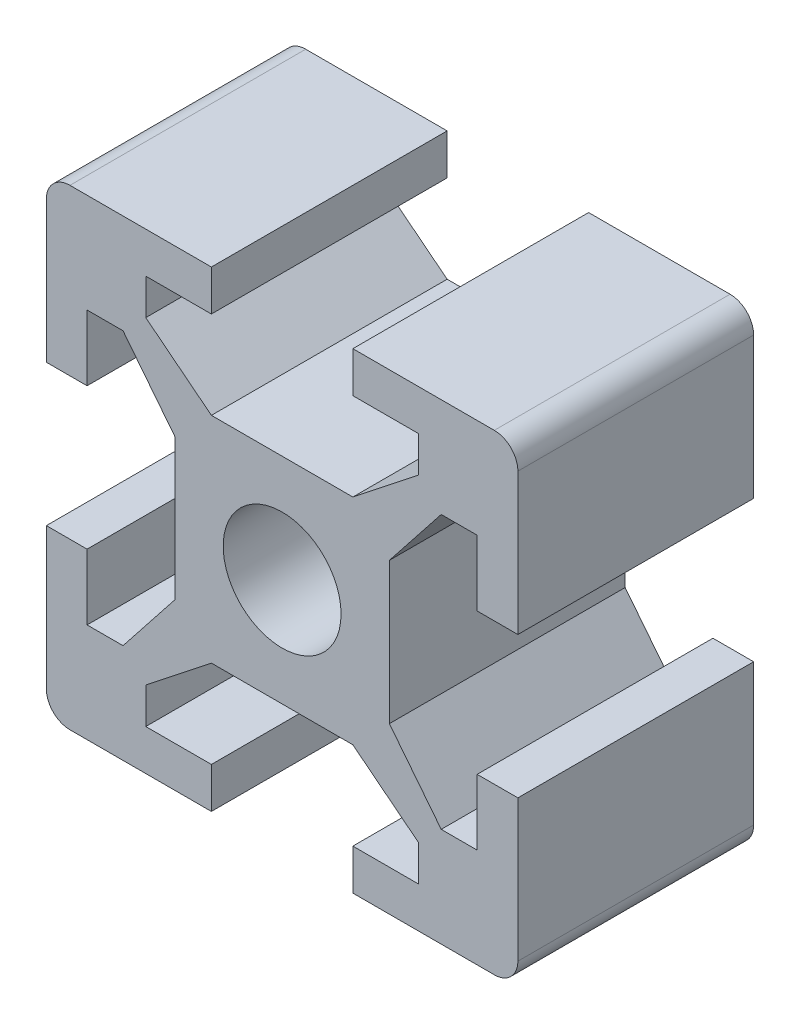
SolidWorks part; units mm, degrees
material "6063-T5"
ref_plane "Front Plane" through (0, 0, 0) normal (0, 0, 1) x (1, 0, 0)
ref_plane "Top Plane" through (0, 0, 0) normal (0, 1, 0) x (1, 0, 0)
ref_plane "Right Plane" through (0, 0, 0) normal (1, 0, 0) x (0, 0, -1)
sketch "Sketch1" plane through (0, 0, 0) normal (0, 0, 1) x (1, 0, 0)
  line L18 (0, 0) -> (0, 20.5117) construction
  line L39 (-10, 10) -> (-3, 10)
  line L41 (10, 10) -> (3, 10)
  line L43 (-10, 10) -> (-10, 3)
  line L45 (-10, -10) -> (-10, -3)
  line L47 (-10, -10) -> (-3, -10)
  line L49 (3, -10) -> (10, -10)
  line L51 (10, -10) -> (10, -3)
  line L53 (10, 3) -> (10, 10)
  line L55 (-3, 10) -> (-3, 8.2726)
  line L56 (-3, 8.2726) -> (-5.7838, 8.2726)
  line L57 (-5.7838, 8.2726) -> (-5.7838, 6.748)
  line L58 (-5.7838, 6.748) -> (-3, 4.5508)
  line L59 (-3, 4.5508) -> (3, 4.5508)
  line L60 (3, 10) -> (3, 8.2726)
  line L61 (3, 8.2726) -> (5.7838, 8.2726)
  line L62 (5.7838, 8.2726) -> (5.7838, 6.748)
  line L63 (5.7838, 6.748) -> (3, 4.5508)
  line L64 (10, 3) -> (8.2726, 3)
  line L65 (8.2726, 3) -> (8.2726, 5.7838)
  line L66 (8.2726, 5.7838) -> (6.748, 5.7838)
  line L67 (10, -3) -> (8.2726, -3)
  line L68 (8.2726, -3) -> (8.2726, -5.7838)
  line L69 (8.2726, -5.7838) -> (6.748, -5.7838)
  line L70 (4.55, -2.9994) -> (4.55, 3.0006)
  line L71 (4.55, -2.9994) -> (6.748, -5.7838)
  line L72 (4.55, 3.0006) -> (6.748, 5.7838)
  line L73 (3, -10) -> (3, -8.2726)
  line L74 (3, -8.2726) -> (5.7838, -8.2726)
  line L75 (5.7838, -8.2726) -> (5.7838, -6.748)
  line L76 (-3, -10) -> (-3, -8.2726)
  line L77 (-3, -8.2726) -> (-5.7838, -8.2726)
  line L78 (-5.7838, -8.2726) -> (-5.7838, -6.748)
  line L79 (2.9994, -4.55) -> (-3.0006, -4.55)
  line L80 (5.7838, -6.748) -> (2.9994, -4.55)
  line L81 (-5.7838, -6.748) -> (-3.0006, -4.55)
  line L82 (-10, -3) -> (-8.2726, -3)
  line L83 (-8.2726, -3) -> (-8.2726, -5.7838)
  line L84 (-8.2726, -5.7838) -> (-6.748, -5.7838)
  line L85 (-10, 3) -> (-8.2726, 3)
  line L86 (-8.2726, 3) -> (-8.2726, 5.7838)
  line L87 (-8.2726, 5.7838) -> (-6.748, 5.7838)
  line L88 (-4.55, -3.0006) -> (-4.55, 2.9994)
  line L89 (-6.748, -5.7838) -> (-4.55, -3.0006)
  line L90 (-4.55, 2.9994) -> (-6.748, 5.7838)
  dimension "D9" = 7
  dimension "D17" = 2.7838
  dimension "D1" = 20
  dimension "D2" = 20
  dimension "D3" = 10
  dimension "D4" = 10
  dimension "D5" = 7
  dimension "D6" = 7
  dimension "D7" = 7
  dimension "D8" = 7
  dimension "D10" = 7
  dimension "D11" = 7
  dimension "D12" = 7
  dimension "D13" = 6
  dimension "D14" = 3
  dimension "D15" = 3.5464
  dimension "D16" = 1.5246
  dimension "D18" = 1.7274
  dimension "D19" = 4.55
  dimension "D20" = 4.55
  dimension "D21" = 4.55
  dimension "D22" = 10
  dimension "D23" = 10
  dimension "D24" = 10
  dimension "D25" = 10
  dimension "D26" = 10
  dimension "D27" = 10
  dimension "D28" = 6
  dimension "D29" = 6
  dimension "D30" = 6
  dimension "D31" = 6
extrude "Boss-Extrude1" add sketch "Sketch1" along normal mid plane 10
sketch "Sketch2" plane through (0, 0, 5) normal (0, 0, 1) x (1, 0, 0)
  circle A0 centre (0, 0) radius 2.5
  dimension "D1" = 5
extrude "Cut-Extrude1" cut sketch "Sketch2" against normal through all both and the other way through all
fillet "Fillet1" radius 1 4 edges at (-10, -10, 0) (10, -10, 0) (10, 10, 0) (-10, 10, 0)
